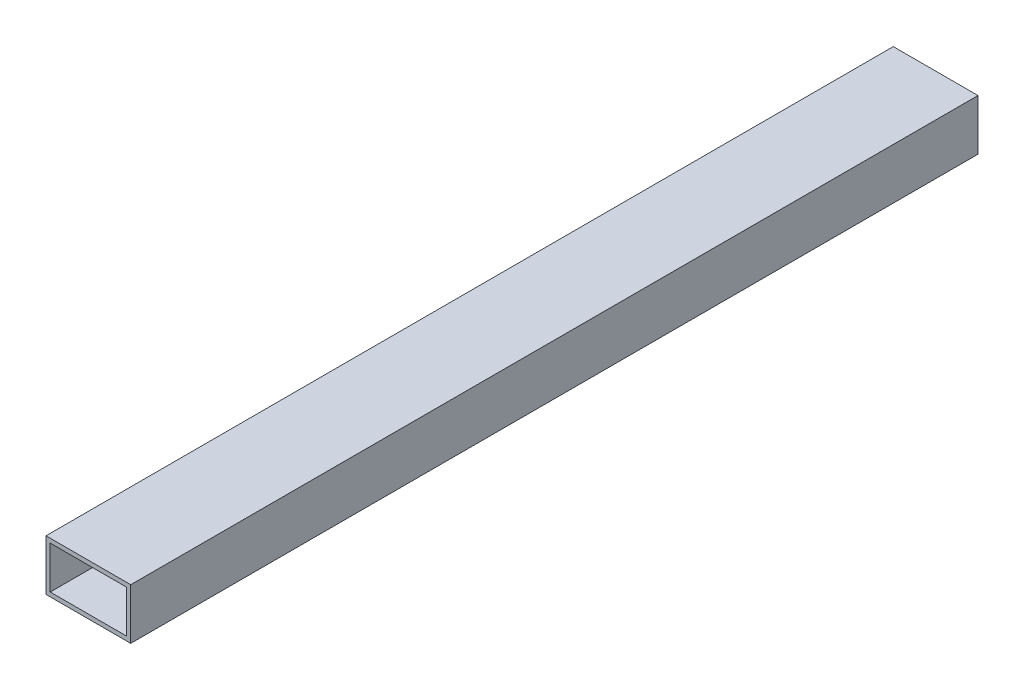
SolidWorks part; units mm, degrees
material "6061-T6 (SS)"
ref_plane "Front" through (0, 0, 0) normal (0, 0, 1) x (1, 0, 0)
ref_plane "Top" through (0, 0, 0) normal (0, 1, 0) x (1, 0, 0)
ref_plane "Right" through (0, 0, 0) normal (1, 0, 0) x (0, 0, -1)
sketch "Sketch1" plane through (0, 0, 0) normal (0, 0, 1) x (1, 0, 0)
  line L0 (-22.5, -12.5) -> (-22.5, 12.5)
  line L1 (-25, -15) -> (25, -15)
  line L2 (-25, -15) -> (-25, 15)
  line L3 (-25, 15) -> (25, 15)
  line L4 (25, -15) -> (25, 15)
  line L5 (-25, -15) -> (25, 15) construction
  line L6 (-25, 15) -> (25, -15) construction
  line L7 (-22.5, 12.5) -> (22.5, 12.5)
  line L8 (22.5, -12.5) -> (22.5, 12.5)
  line L9 (-22.5, -12.5) -> (22.5, -12.5)
  point P0 (0, 0)
  dimension "D2" = 50
  dimension "D3" = 30
  dimension "D1" = 2.5
extrude "Boss-Extrude1" add sketch "Sketch1" along normal mid plane 500
